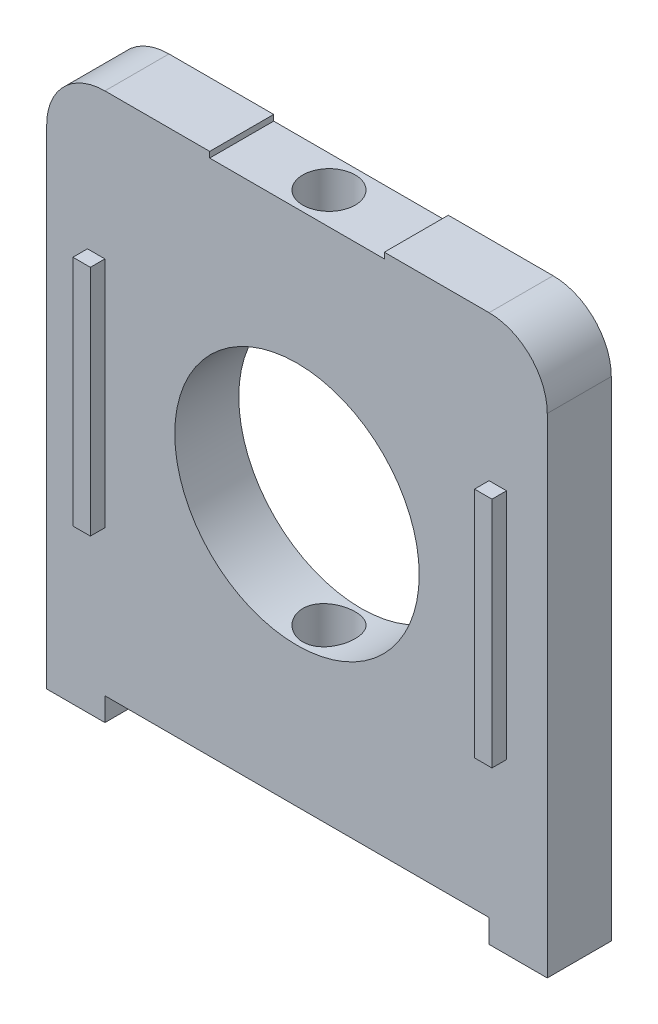
SolidWorks part; units mm, degrees
ref_plane "Front Plane" through (0, 0, 0) normal (0, 0, 1) x (1, 0, 0)
ref_plane "Top Plane" through (0, 0, 0) normal (0, 1, 0) x (1, 0, 0)
ref_plane "Right Plane" through (0, 0, 0) normal (1, 0, 0) x (0, 0, -1)
sketch "Sketch1" plane through (0, 0, 0) normal (0, 0, 1) x (1, 0, 0)
  line L1 (-21.5, 22.5) -> (21.5, 22.5)
  line L2 (-21.5, 22.5) -> (-21.5, -22.5)
  line L3 (-21.5, -22.5) -> (21.5, -22.5)
  line L4 (21.5, 22.5) -> (21.5, -22.5)
  line L5 (0, -22.5) -> (0, 22.5) construction
  line L6 (-21.5, 0) -> (21.5, 0) construction
  circle A0 centre (0, 0) radius 10.5
  dimension "D1" = 21
  dimension "D2" = 43
  dimension "D3" = 45
extrude "Boss-Extrude1" add sketch "Sketch1" along normal mid plane 5.5
fillet "Fillet1" radius 5 2 edges at (-21.5, 22.5, 0) (21.5, 22.5, 0)
sketch "Sketch2" plane through (0, 0, 2.75) normal (0, 0, 1) x (1, 0, 0)
  line L0 (16.5, 22.5) -> (-16.5, 22.5) construction
  line L1 (7.5, 22.5) -> (-7.5, 22.5)
  line L2 (7.5, 22.5) -> (7.5, 22)
  line L3 (7.5, 22) -> (-7.5, 22)
  line L4 (-7.5, 22.5) -> (-7.5, 22)
  point P6 (0, 22.5)
  dimension "D1" = 15
  dimension "D2" = 0.5
extrude "Cut-Extrude1" cut sketch "Sketch2" against normal blind 10
hole_wizard "M4 Clearance Hole1" positions "Sketch3" profile "Sketch4" hole size "M4" standard "ISO" end condition through all
sketch "Sketch3" plane through (0, 22, 0) normal (0, 1, 0) x (1, 0, 0)
  point P0 (0, 0)
sketch "Sketch4" plane through (0, 22, 0) normal (1, 0, 0) x (0, 0, 1)
  line L0 (0, 0) -> (0, 44.5)
  line L1 (0, 44.5) -> (2.25, 44.5)
  line L2 (2.25, 44.5) -> (2.25, 0)
  line L5 (2.25, 0) -> (0, 0)
  line L11 (0, -6.35) -> (0, 107.95) construction
  dimension "Thru Hole Dia." = 4.5
  dimension "Thru Hole Depth" = 44.5
sketch "Sketch5" plane through (0, 0, 0) normal (0, 0, 1) x (1, 0, 0)
  line L0 (0, 0) -> (0, -10.5) construction
  line L1 (-18, 10) -> (-16.5, 10)
  line L2 (-18, 10) -> (-18, -10)
  line L3 (-18, -10) -> (-16.5, -10)
  line L4 (-16.5, 10) -> (-16.5, -10)
  line L5 (-21.5, 17.5) -> (-21.5, -22.5) construction
  line L6 (18, -10) -> (16.5, -10)
  line L7 (16.5, 10) -> (16.5, -10)
  line L8 (18, 10) -> (16.5, 10)
  line L9 (18, 10) -> (18, -10)
  circle A0 centre (0, 0) radius 10.5 construction
  point P9 (-16.5, 0)
  dimension "D1" = 1.5
  dimension "D2" = 20
  dimension "D3" = 3.5
extrude "Boss-Extrude2" add sketch "Sketch5" along normal mid plane 8
sketch "Sketch6" plane through (0, 0, 0) normal (0, 0, 1) x (1, 0, 0)
  line L1 (-21.5, -22.5) -> (-16.5, -22.5)
  line L2 (-21.5, -22.5) -> (-21.5, -24.5)
  line L3 (-21.5, -24.5) -> (-16.5, -24.5)
  line L4 (-16.5, -22.5) -> (-16.5, -24.5)
  line L5 (21.5, -22.5) -> (16.5, -22.5)
  line L6 (21.5, -22.5) -> (21.5, -24.5)
  line L7 (21.5, -24.5) -> (16.5, -24.5)
  line L8 (16.5, -22.5) -> (16.5, -24.5)
  dimension "D1" = 2
  dimension "D2" = 5
  dimension "D3" = 2
  dimension "D4" = 5
extrude "Boss-Extrude3" add sketch "Sketch6" along normal mid plane 5.5
